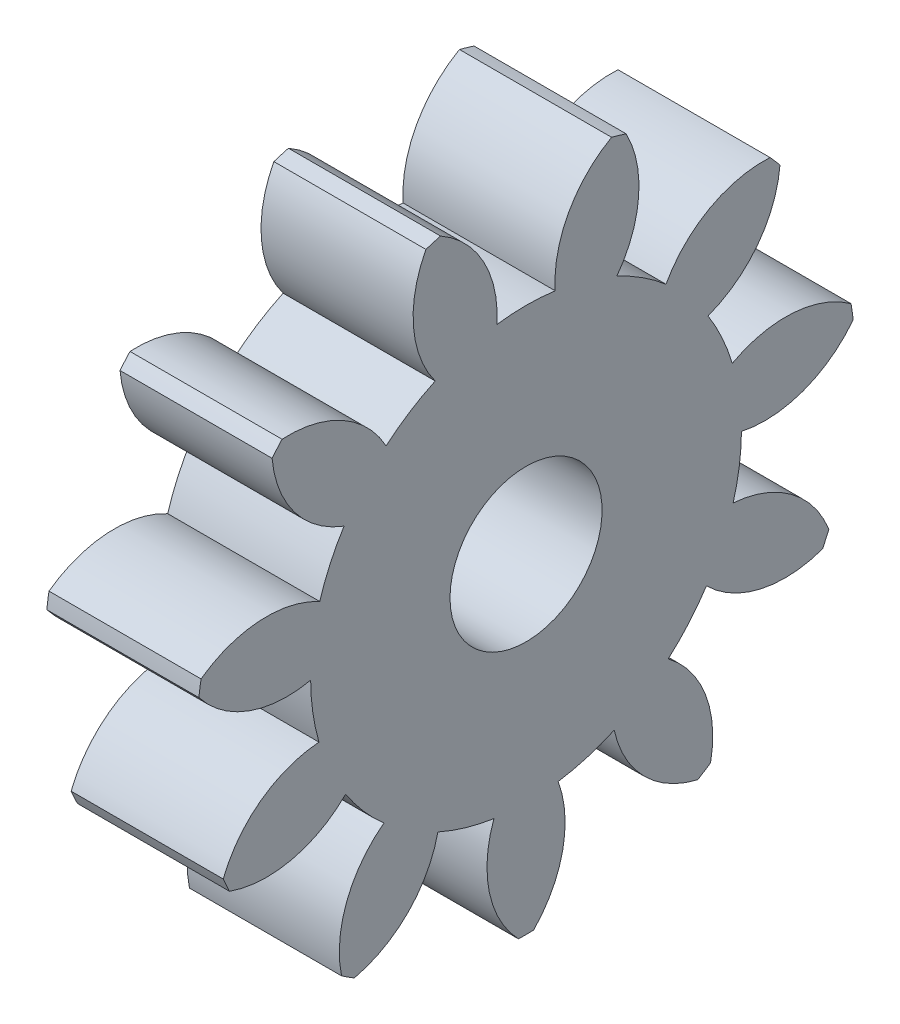
SolidWorks part; units mm, degrees
ref_plane "Plane1" through (0, 0, 0) normal (0, 0, 1) x (1, 0, 0)
ref_plane "Plane2" through (0, 0, 0) normal (0, 1, 0) x (1, 0, 0)
ref_plane "Plane3" through (0, 0, 0) normal (1, 0, 0) x (0, 0, -1)
sketch "HoldingSke" plane through (0, 0, 0) normal (0, 1, 0) x (1, 0, 0)
  line L0 (0, 0) -> (0.9816, -0.1908)
  line L1 (-15, 0) -> (100, 0) construction
  line L2 (0, 0) -> (-2.1039, 2.3779)
  line L3 (0, 0) -> (-11.863, 4.5341)
  line L4 (0, 0) -> (8.4773, 1.6478)
  line L5 (0, 0) -> (-46.8476, -17.4728)
  line L6 (0, 0) -> (-2.4869, -1.6779)
  line L7 (-2.1039, 2.3779) -> (8.6586, 51.2059)
  line L8 (-76.2, 54.61) -> (-75.7, 54.61)
  line L9 (-71.009, 38.7566) -> (-53.1078, 45.2721)
  line L10 (-76.2, 71.12) -> (104.1128, 71.12)
  line L11 (0, 0) -> (-3, 0)
  line L12 (-76.2, 101.6) -> (-76.162, 101.6)
  line L13 (24.9733, 27.94) -> (52.9518, 28.4284)
  line L14 (24.9733, 27.94) -> (24.9743, 27.94)
  line L15 (24.9733, 27.94) -> (100.4006, 29.5858)
  line L16 (-63.627, -1) -> (-12.827, -1)
  circle A0 centre (0, 0) radius 1.5
  circle A1 centre (0, 0) radius 4.249
  circle A2 centre (0, 0) radius 37.5
  circle A3 centre (0, 0) radius 1.5
  dimension "MHD" = 8.498
  dimension "Hub_dia" = 75
  dimension "Bore" = 3
  dimension "MBD" = 3
  dimension "Num_teeth" = 11
  dimension "Pitch" = 1
  dimension "Overall_len" = 50
  dimension "Show_teeth" = 11
  dimension "Thickness" = 3
  dimension "OAL" = 50.0001
  dimension "T_dim" = 0.5
  dimension "Ap" = 20
  dimension "H" = 19.05
  dimension "Pitch_radius" = 180.3128
  dimension "Width" = 3
  dimension "Backlash" = 0.038
  dimension "Addendum_fac" = 1
  dimension "Dedendum_fac" = 1.25
  dimension "Clearance_fac" = 0.25
  dimension "Dedendum_add" = 0.001
  dimension "Module" = 1
sketch "BasProSke" plane through (0, 0, 0) normal (0, 1, 0) x (1, 0, 0)
  line L0 (-10, 0) -> (60, 0) construction
  line L1 (0, 0) -> (0, 6.5)
  line L2 (0, 0) -> (3, 0)
  line L3 (3, 0) -> (3, 6.5)
  line L4 (3, 6.5) -> (0, 6.5)
  dimension "Thickness" = 3
  dimension "Diameter" = 13
revolve "Base-Revolve" add sketch "BasProSke" angle 360 about L0
sketch "TooCutSke" plane through (0, 0, 0) normal (1, 0, 0) x (0, 0, -1)
  line L1 (0, 0) -> (0, 107) construction
  line L2 (0, 0) -> (-0.8491, 5.4341) construction
  line L3 (0, 0) -> (-3.0727, 10.4645) construction
  line L4 (-0.8491, 5.4341) -> (-1.5363, 5.2323) construction
  arc A0 (0.576, 4.2098) -> (-0.576, 4.2098) centre (0, 0) ccw
  arc A1 (1.7187, 6.295) -> (-1.7187, 6.295) centre (0, 0) ccw
  circle A2 centre (0, 0) radius 5.5 construction
  circle A3 centre (0, 0) radius 5.1683 construction
  arc A4 (-0.576, 4.2098) -> (-1.7187, 6.295) centre (-2.7707, 4.3629) ccw
  arc A5 (1.7187, 6.295) -> (0.576, 4.2098) centre (2.7707, 4.3629) ccw
  dimension "Root_dia" = 8.498
  dimension "Overcut_dia" = 13.0508
  dimension "Pitch_dia" = 11
  dimension "Base_dia" = 10.3366
  dimension "Flank_rad" = 2.2
  dimension "Half_ang" = 16.364
  dimension "Half_CT" = 0.7162
extrude "ToothCut" cut sketch "TooCutSke" along normal through all
fillet "Breaks" [suppressed] radius 0.02
fillet "RootFillets" [suppressed] radius 0.251
pattern_circular "TeethCuts" count 11 every 32.727 about axis through (-10, 0, 0) along (1, 0, 0) of "ToothCut", "RootFillets", "Breaks"
sketch "HubNeaOneSke" plane through (0, 0, 0) normal (-1, 0, 0) x (0, 0, 1)
  circle A0 centre (0, 0) radius 4.249
  dimension "Diameter" = 8.498
extrude "HubNearOne" [suppressed] add sketch "HubNeaOneSke" along normal blind 47.0001
sketch "HubNeaBotSke" plane through (0, 0, 0) normal (-1, 0, 0) x (0, 0, 1)
  circle A0 centre (0, 0) radius 4.249
  dimension "Diameter" = 8.498
extrude "HubNearBoth" [suppressed] add sketch "HubNeaBotSke" along normal blind 23.5
ref_plane "FarPln" through (3, 0, 0) normal (1, 0, 0) x (0, 0, -1)
sketch "HubFarSke" plane through (3, 0, 0) normal (1, 0, 0) x (0, 0, -1)
  circle A0 centre (0, 0) radius 4.249
  dimension "Diameter" = 8.498
extrude "HubFar" [suppressed] add sketch "HubFarSke" along normal blind 23.5
sketch "BorSke" plane through (0, 0, 0) normal (1, 0, 0) x (0, 0, -1)
  circle A0 centre (0, 0) radius 1.5
  dimension "Diameter" = 3
extrude "Bore" cut sketch "BorSke" along normal mid plane 100.0001
sketch "KeySke" plane through (0, 0, 0) normal (1, 0, 0) x (0, 0, -1)
  line L0 (-0.6, 0) -> (-0.6, 2)
  line L1 (-0.6, 2) -> (0.6, 2)
  line L2 (0.6, 2) -> (0.6, 0)
  line L3 (0, 0) -> (0, 34) construction
  line L4 (-0.6, 0) -> (0.6, 0)
  dimension "Offset" = 2
  dimension "Width" = 1.2
extrude "Keyway" [suppressed] cut sketch "KeySke" along normal mid plane 100.0001
pattern_circular "Keyway2" [suppressed] count 2 every 90 about axis through (-10, 0, 0) along (1, 0, 0)
equation "' \"Module@HoldingSke\" = 6.35"
equation "' \"Num_teeth@HoldingSke\" = 12"
equation "' \"Ap@HoldingSke\" =  20"
equation "' \"Ap@HoldingSke\" = 20"
equation "' \"Width@HoldingSke\" = 0.5 * 25.4"
equation "' \"Hub_dia@HoldingSke\"= 1 * 25.4"
equation "' \"Hub_dia@HoldingSke\" = 1 * 25.4"
equation "' \"Overall_len@HoldingSke\" = 1.0 * 25.4"
equation "' \"Bore@HoldingSke\" = 0.75 * 25.4"
equation "' \"T_dim@HoldingSke\" = 0.1 * 25.4"
equation "' \"Width@KeySke\" = 0.25 * 25.4"
equation "' \"Show_teeth@HoldingSke\" = 13"
equation "' \"Backlash@HoldingSke\" = 0.009 * 25.4"
equation "' \"Addendum_fac@HoldingSke\" = 1.0"
equation "' \"Dedendum_fac@HoldingSke\" = 1.25"
equation "' \"Dedendum_add@HoldingSke\" = 0.00005 * 25.4"
equation "' \"Clearance_fac@HoldingSke\" = 0.25"
equation "\"Pitch@HoldingSke\" = 1 / \"Module@HoldingSke\""
equation "\"Overcut_dia@TooCutSke\" = (\"Num_teeth@HoldingSke\" + 2 * \"Addendum_fac@HoldingSke\") / \"Pitch@HoldingSke\" + 0.002 * 25.4"
equation "\"Pitch_dia@TooCutSke\" = \"Num_teeth@HoldingSke\" / \"Pitch@HoldingSke\""
equation "\"Base_dia@TooCutSke\" = \"Num_teeth@HoldingSke\" / \"Pitch@HoldingSke\" * cos((\"Ap@HoldingSke\"  * 3.14159265 / 180))"
equation "\"Root_dia@TooCutSke\" = (\"Num_teeth@HoldingSke\" + 2) / \"Pitch@HoldingSke\" - 2 * (\"Addendum_fac@HoldingSke\" + \"Dedendum_fac@HoldingSke\") / \"Pitch@HoldingSke\" - \"Dedendum_add@HoldingSke\" * 2"
equation "\"Half_ang@TooCutSke\" = 180 / \"Num_teeth@HoldingSke\""
equation "\"Half_CT@TooCutSke\" = \"Num_teeth@HoldingSke\" / \"Pitch@HoldingSke\" * sin((3.14159265 / 2 / \"Num_teeth@HoldingSke\")) / 2 - 7 * \"Backlash@HoldingSke\" / 4"
equation "\"Flank_rad@TooCutSke\" = \"Num_teeth@HoldingSke\" / \"Pitch@HoldingSke\" / 5"
equation "\"Radius@RootFillets\" = \"Clearance_fac@HoldingSke\" / \"Pitch@HoldingSke\" + \"Dedendum_add@HoldingSke\""
equation "\"Break_rad@Breaks\" = 0.02 / \"Pitch@HoldingSke\""
equation "\"Thickness@HoldingSke\" = \"Width@HoldingSke\""
equation "\"OAL@HoldingSke\" = \"Thickness@HoldingSke\""
equation "\"MHD@HoldingSke\" = (\"Num_teeth@HoldingSke\" + 2) / \"Pitch@HoldingSke\" - 2 * (\"Addendum_fac@HoldingSke\" + \"Dedendum_fac@HoldingSke\")  / \"Pitch@HoldingSke\" - \"Dedendum_add@HoldingSke\" * 2"
equation "\"MBD@HoldingSke\" = (\"Num_teeth@HoldingSke\" + 2) / \"Pitch@HoldingSke\" - 2 * (\"Addendum_fac@HoldingSke\" + \"Dedendum_fac@HoldingSke\")  / \"Pitch@HoldingSke\" - \"Dedendum_add@HoldingSke\" * 2 - 0.002 * 25.4"
equation "\"MHD@HoldingSke\" = ((sgn( \"MHD@HoldingSke\" - \"Hub_dia@HoldingSke\" )-1)*( \"MHD@HoldingSke\" - \"Hub_dia@HoldingSke\" ))/-2+ \"Hub_dia@HoldingSke\""
equation "\"MBD@HoldingSke\" = ((sgn( \"MBD@HoldingSke\" - \"Bore@HoldingSke\" )-1)*( \"MBD@HoldingSke\" - \"Bore@HoldingSke\" ))/-2+ \"Bore@HoldingSke\""
equation "\"OAL@HoldingSke\" = ((sgn( \"OAL@HoldingSke\" - \"Overall_len@HoldingSke\" )+1)*( \"OAL@HoldingSke\" - \"Overall_len@HoldingSke\" ))/2 + \"Overall_len@HoldingSke\" + 0.000002 * 25.4"
equation "\"Num_teeth@TeethCuts\" = int( \"Show_teeth@HoldingSke\" ) + 1"
equation "\"Num_teeth@TeethCuts\" = ((sgn( \"Num_teeth@TeethCuts\" - \"Num_teeth@HoldingSke\" )-1)*( \"Num_teeth@TeethCuts\" - \"Num_teeth@HoldingSke\" ))/-2+ \"Num_teeth@HoldingSke\""
equation "\"Num_teeth@TeethCuts\" = ((sgn( \"Num_teeth@TeethCuts\" - 2.0)+1)*( \"Num_teeth@TeethCuts\" - 2.0))/2 +2.0"
equation "\"Angle@TeethCuts\" = 360.0 / \"Num_teeth@HoldingSke\""
equation "\"Diameter@BasProSke\" = (\"Num_teeth@HoldingSke\" + 2 * \"Addendum_fac@HoldingSke\") / \"Pitch@HoldingSke\""
equation "\"Thickness@BasProSke\"  = \"Thickness@HoldingSke\""
equation "' \"Fillet_rad@BasProSke\" =  \"Thickness@HoldingSke\" * 0.05"
equation "' \"Fillet_rad@BasProSke\" = \"Thickness@HoldingSke\" * 0.05"
equation "\"MHD@HoldingSke\" = ((sgn( \"MHD@HoldingSke\" - \"Root_dia@TooCutSke\" )-1)*( \"MHD@HoldingSke\" - \"Root_dia@TooCutSke\" ))/-2+ \"Root_dia@TooCutSke\""
equation "\"Diameter@HubNeaOneSke\" = \"MHD@HoldingSke\""
equation "\"Length@HubNearOne\" = \"OAL@HoldingSke\" - \"Thickness@BasProSke\""
equation "\"Diameter@HubNeaBotSke\" = \"MHD@HoldingSke\""
equation "\"Length@HubNearBoth\" = ( \"OAL@HoldingSke\" - \"Thickness@BasProSke\" ) / 2.0"
equation "\"Thickness@FarPln\" = \"Thickness@BasProSke\""
equation "\"Diameter@HubFarSke\" = \"MHD@HoldingSke\""
equation "\"Length@HubFar\" = ( \"OAL@HoldingSke\" - \"Thickness@BasProSke\" ) / 2.0"
equation "\"Diameter@BorSke\" = \"MBD@HoldingSke\""
equation "\"D1@Bore\" = \"OAL@HoldingSke\" * 2.0"
equation "\"D1@Keyway\" = \"OAL@HoldingSke\" * 2.0"
equation "\"Offset@KeySke\" = \"T_dim@HoldingSke\" + \"MBD@HoldingSke\" / 2.0"
